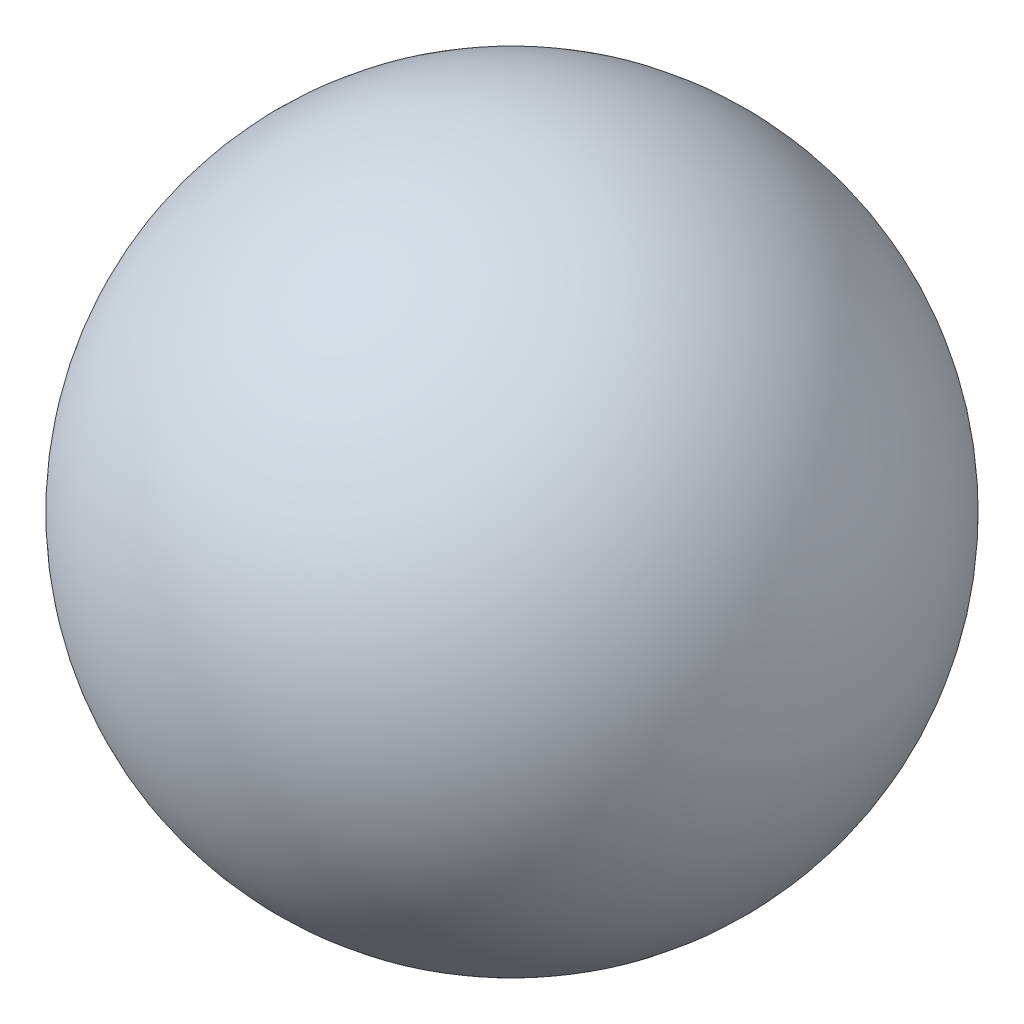
SolidWorks part; units mm, degrees
material "Alloy Steel (SS)"
ref_plane "Front Plane" through (0, 0, 0) normal (0, 0, 1) x (1, 0, 0)
ref_plane "Top Plane" through (0, 0, 0) normal (0, 1, 0) x (1, 0, 0)
ref_plane "Right Plane" through (0, 0, 0) normal (1, 0, 0) x (0, 0, -1)
sketch "Sketch1" plane through (0, 0, 0) normal (0, 0, 1) x (1, 0, 0)
  line L0 (0, -19.05) -> (0, 19.05) construction
  line L1 (0, -19.05) -> (0, 19.05)
  arc A0 (0, -19.05) -> (0, 19.05) centre (0, 0) ccw
  point P3 (0, 0)
  dimension "D1" = 38.1
revolve "Revolve1" add sketch "Sketch1" angle 360 about L0
